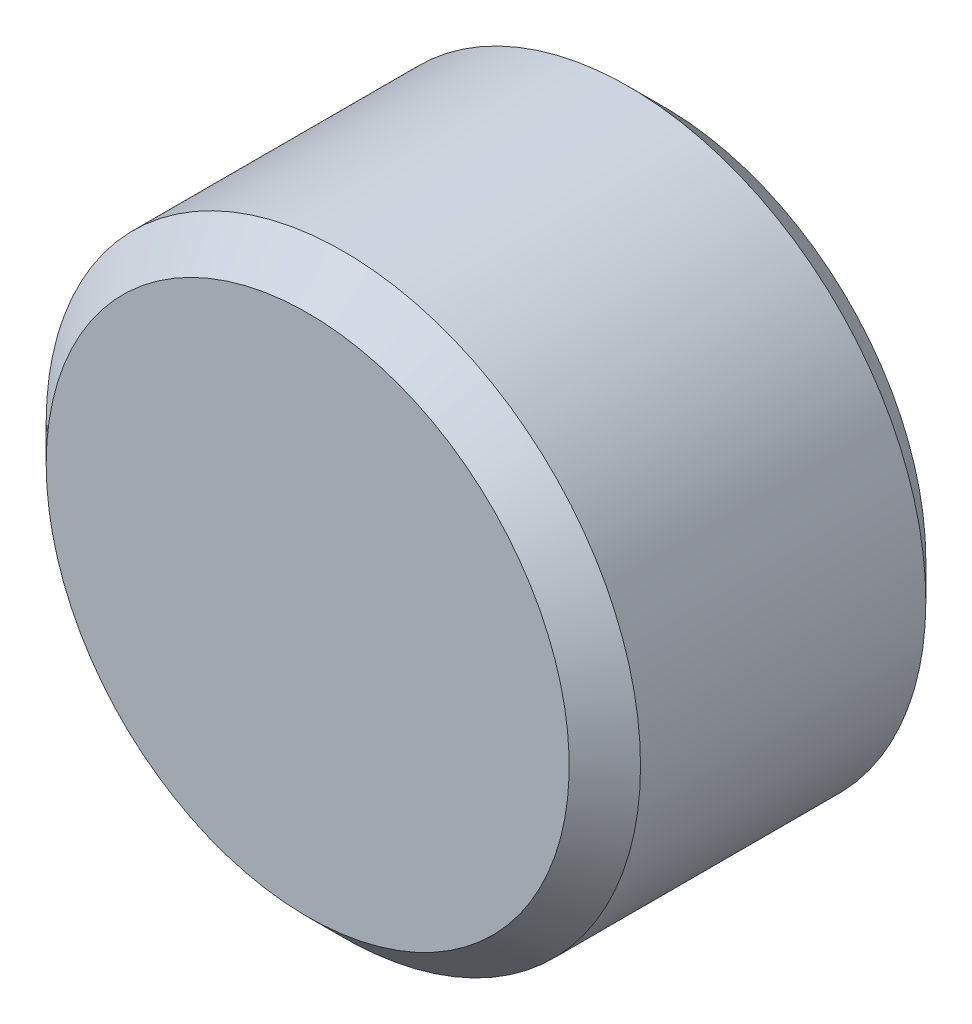
SolidWorks part; units mm, degrees
ref_plane "Front" through (0, 0, 0) normal (0, 0, 1) x (1, 0, 0)
ref_plane "Top" through (0, 0, 0) normal (0, 1, 0) x (1, 0, 0)
ref_plane "Right" through (0, 0, 0) normal (1, 0, 0) x (0, 0, -1)
sketch "Эскиз1" plane through (0, 0, 0) normal (0, 0, 1) x (1, 0, 0)
  circle A0 centre (0, 0) radius 2.5
extrude "Бобышка-Вытянуть1" add sketch "Эскиз1" along normal blind 3
chamfer "Фаска1" distance 0.3 angle 45 2 edges at (2.5, 0, 3) (2.5, 0, 0)
